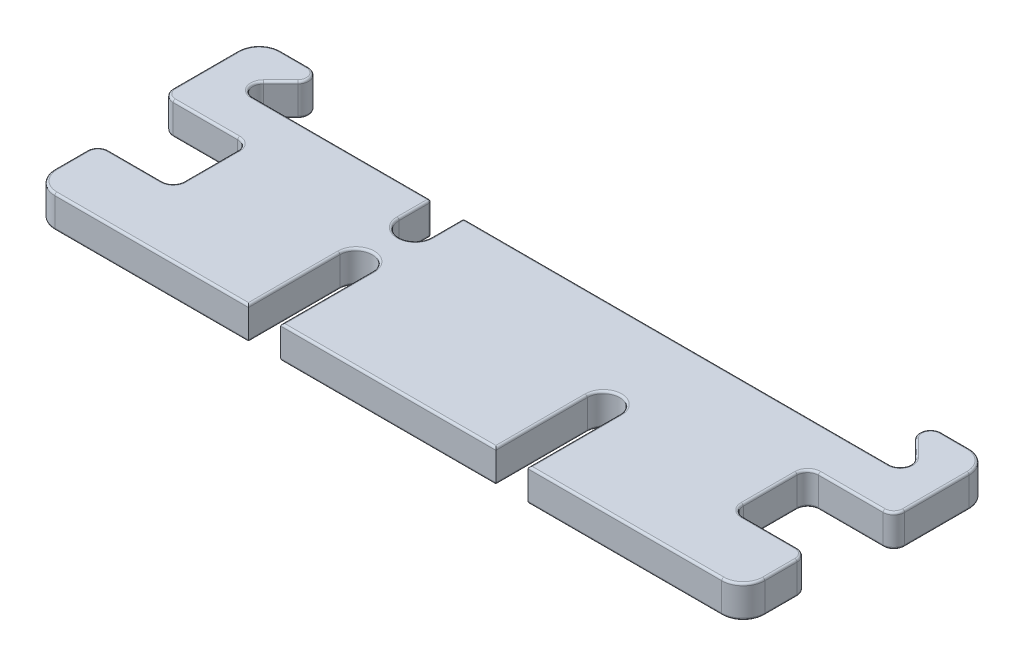
SolidWorks part; units mm, degrees
ref_plane "Front Plane" through (0, 0, 0) normal (0, 0, 1) x (1, 0, 0)
ref_plane "Top Plane" through (0, 0, 0) normal (0, 1, 0) x (1, 0, 0)
ref_plane "Right Plane" through (0, 0, 0) normal (1, 0, 0) x (0, 0, -1)
sketch "Sketch1" plane through (0, 0, 0) normal (0, 1, 0) x (1, 0, 0)
  line L0 (0, 0) -> (0, 17) construction
  line L1 (10, 0) -> (-10, 0)
  line L2 (-10, 0) -> (-10, 8.5)
  line L3 (-13, 8.5) -> (-13, 0)
  line L4 (-13, 0) -> (-31, 0)
  line L5 (-33, 2) -> (-33, 5)
  line L6 (-32, 6) -> (-27, 6)
  line L7 (-26, 7) -> (-26, 12)
  line L8 (-27, 13) -> (-33, 13)
  line L9 (-34, 14) -> (-34, 20)
  line L10 (-32, 22) -> (-29.4142, 22)
  line L11 (-28.7071, 20.2929) -> (-30.2929, 18.7071)
  line L12 (-29.5858, 17) -> (-13, 17)
  line L13 (28.7071, 20.2929) -> (30.2929, 18.7071)
  line L14 (32, 22) -> (29.4142, 22)
  line L15 (34, 14) -> (34, 20)
  line L16 (27, 13) -> (33, 13)
  line L17 (26, 7) -> (26, 12)
  line L18 (32, 6) -> (27, 6)
  line L19 (33, 2) -> (33, 5)
  line L20 (13, 0) -> (31, 0)
  line L21 (13, 8.5) -> (13, 0)
  line L22 (10, 0) -> (10, 8.5)
  line L23 (-13, 14) -> (-13, 17)
  line L24 (-10, 14) -> (-10, 17)
  line L25 (-10, 17) -> (29.5858, 17)
  arc A0 (-10, 8.5) -> (-13, 8.5) centre (-11.5, 8.5) ccw
  arc A1 (-27, 6) -> (-26, 7) centre (-27, 7) ccw
  arc A2 (-26, 12) -> (-27, 13) centre (-27, 12) ccw
  arc A3 (-33, 5) -> (-32, 6) centre (-32, 5) cw
  arc A4 (-33, 13) -> (-34, 14) centre (-33, 14) cw
  arc A5 (-29.4142, 22) -> (-28.7071, 20.2929) centre (-29.4142, 21) cw
  arc A6 (-30.2929, 18.7071) -> (-29.5858, 17) centre (-29.5858, 18) ccw
  arc A7 (-31, 0) -> (-33, 2) centre (-31, 2) cw
  arc A8 (-34, 20) -> (-32, 22) centre (-32, 20) cw
  arc A9 (34, 20) -> (32, 22) centre (32, 20) ccw
  arc A10 (31, 0) -> (33, 2) centre (31, 2) ccw
  arc A11 (30.2929, 18.7071) -> (29.5858, 17) centre (29.5858, 18) cw
  arc A12 (29.4142, 22) -> (28.7071, 20.2929) centre (29.4142, 21) ccw
  arc A13 (33, 13) -> (34, 14) centre (33, 14) ccw
  arc A14 (33, 5) -> (32, 6) centre (32, 5) ccw
  arc A15 (26, 12) -> (27, 13) centre (27, 12) cw
  arc A16 (27, 6) -> (26, 7) centre (27, 7) cw
  arc A17 (10, 8.5) -> (13, 8.5) centre (11.5, 8.5) cw
  arc A18 (-13, 14) -> (-10, 14) centre (-11.5, 14) ccw
  point P18 (-26, 6)
  point P21 (-26, 13)
  point P24 (-33, 6)
  point P29 (-27, 22)
  point P34 (-33, 0)
  point P37 (-34, 22)
  point P67 (34, 22)
  point P68 (33, 0)
  point P69 (27, 22)
  point P70 (33, 6)
  point P71 (26, 13)
  point P72 (26, 6)
  dimension "D2" = 1.5
  dimension "D13" = 1
  dimension "D14" = 2
  dimension "D15" = 1.5
  dimension "D1" = 17
  dimension "D3" = 8.5
  dimension "D4" = 10
  dimension "D5" = 6
  dimension "D6" = 7
  dimension "D7" = 22
  dimension "D8" = 45
  dimension "D9" = 7
  dimension "D10" = 33
  dimension "D11" = 34
  dimension "D12" = 26
  dimension "D17" = 17
  dimension "D18" = 3
extrude "Boss-Extrude1" add sketch "Sketch1" along normal blind 3
ref_plane "Plane1" through (0, 0, -8.5) normal (0, 0, 1) x (0, -1, 0)
ref_plane "Plane2" through (0, 0, -14) normal (0, 0, 1) x (0, -1, 0)
fillet "Fillet1" radius 0.2 90 edges at (-11.5, 3, -10) (-13, 3, -4.25) (-22, 3, 0) (-32.4142, 3, -0.5858) (-33, 3, -3.5) (-32.7071, 3, -5.7071) (-29.5, 3, -6) (-26.2929, 3, -6.2929) (-26, 3, -9.5) (-26.2929, 3, -12.7071) (-30, 3, -13) (-33.7071, 3, -13.2929) (-34, 3, -17) (-33.4142, 3, -21.4142) (-30.7071, 3, -22) (-28.4903, 3, -21.3827) (-29.5, 3, -19.5) (-30.5097, 3, -17.6173) (-21.2929, 3, -17) (-13, 3, -15.5) (-11.5, 3, -12.5) (-10, 3, -15.5) (9.7929, 3, -17) (30.5097, 3, -17.6173) (29.5, 3, -19.5) (28.4903, 3, -21.3827) (30.7071, 3, -22) (33.4142, 3, -21.4142) (34, 3, -17) (33.7071, 3, -13.2929) (30, 3, -13) (26.2929, 3, -12.7071) (26, 3, -9.5) (26.2929, 3, -6.2929) (29.5, 3, -6) (32.7071, 3, -5.7071) (33, 3, -3.5) (32.4142, 3, -0.5858) (22, 3, 0) (13, 3, -4.25) (11.5, 3, -10) (10, 3, -4.25) (0, 3, 0) (-10, 3, -4.25) (0, 0, 0) (10, 0, -4.25) (11.5, 0, -10) (13, 0, -4.25) (22, 0, 0) (32.4142, 0, -0.5858) (33, 0, -3.5) (32.7071, 0, -5.7071) (29.5, 0, -6) (26.2929, 0, -6.2929) (26, 0, -9.5) (26.2929, 0, -12.7071) (30, 0, -13) (33.7071, 0, -13.2929) (34, 0, -17) (33.4142, 0, -21.4142) (30.7071, 0, -22) (28.4903, 0, -21.3827) (29.5, 0, -19.5) (30.5097, 0, -17.6173) (9.7929, 0, -17) (-10, 0, -15.5) (-11.5, 0, -12.5) (-13, 0, -15.5) (-21.2929, 0, -17) (-30.5097, 0, -17.6173) (-29.5, 0, -19.5) (-28.4903, 0, -21.3827) (-30.7071, 0, -22) (-33.4142, 0, -21.4142) (-34, 0, -17) (-33.7071, 0, -13.2929) (-30, 0, -13) (-26.2929, 0, -12.7071) (-26, 0, -9.5) (-26.2929, 0, -6.2929) (-29.5, 0, -6) (-32.7071, 0, -5.7071) (-33, 0, -3.5) (-32.4142, 0, -0.5858) (-22, 0, 0) (-13, 0, -4.25) (-11.5, 0, -10) (-10, 0, -4.25) (-10, 1.5, -17) (-13, 1.5, -17)
